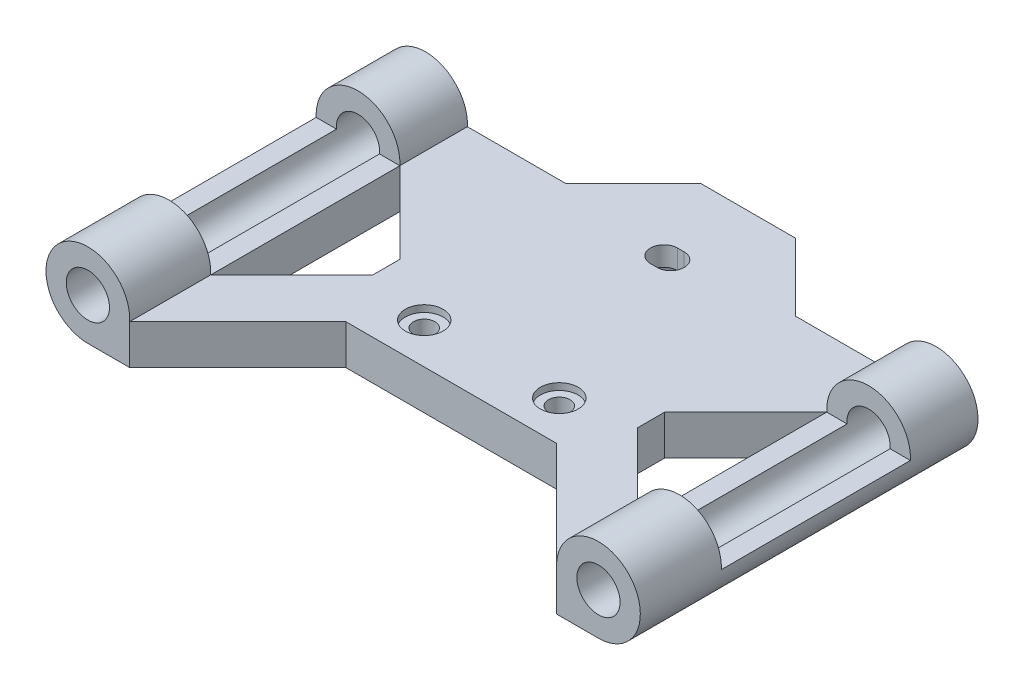
SolidWorks part; units mm, degrees
ref_plane "前视基准面" through (0, 0, 0) normal (0, 0, 1) x (1, 0, 0)
ref_plane "上视基准面" through (0, 0, 0) normal (0, 1, 0) x (1, 0, 0)
ref_plane "右视基准面" through (0, 0, 0) normal (1, 0, 0) x (0, 0, -1)
other "Configuration Table"
sketch "草图1" plane through (0, 0, 0) normal (0, 0, 1) x (1, 0, 0)
  line L0 (-46.6478, 2.4292) -> (-8.8478, 2.4292)
  line L1 (-43.5517, 5.3742) -> (-11.9439, 5.3742)
  line L3 (-37.4778, 5.3742) -> (-18.0178, 5.3742) construction
  circle A0 centre (-46.6478, 5.5292) radius 1.6
  circle A1 centre (-8.8478, 5.5292) radius 1.6
  circle A2 centre (-46.6478, 5.5292) radius 3.1
  circle A3 centre (-8.8478, 5.5292) radius 3.1
  circle A4 centre (-46.6478, 5.5292) radius 1.55 construction
  circle A5 centre (-8.8478, 5.5292) radius 1.525 construction
  dimension "D1" = 3.2
  dimension "D2" = 1.5
extrude "凸台-拉伸1" add sketch "草图1" along normal blind 25 contours A2 A0 | A3 L1 A2 L0 | A3 A1
sketch "草图2" plane through (0, 5.3742, 0) normal (0, 1, 0) x (1, 0, 0)
  line L0 (-19.2478, 0) -> (-24.2478, 5)
  line L1 (-43.5517, 0) -> (-11.9439, 0) construction
  line L2 (-24.2478, 5) -> (-31.2478, 5)
  line L4 (-31.2478, 5) -> (-36.2478, 0)
  line L6 (-27.7478, 17.7449) -> (-27.7478, -46.0927) construction
  line L9 (-43.5478, -25) -> (-43.5478, 0) construction
  line L10 (-11.9478, 0) -> (-11.9478, -25) construction
  line L11 (-36.2478, 0) -> (-19.2478, 0)
  dimension "D1" = 5
  dimension "D2" = 7
  dimension "D3" = 45
extrude "凸台-拉伸2" add sketch "草图2" against normal up to surface (2.945 mm away)
sketch "草图3" plane through (0, 5.3742, 0) normal (0, 1, 0) x (1, 0, 0)
  line L0 (-27.9978, -1) -> (-27.4978, -1) construction
  line L1 (-27.9978, 0) -> (-27.4978, 0)
  line L2 (-27.9978, -2) -> (-27.4978, -2)
  line L3 (-24.2478, 5) -> (-31.2478, 5) construction
  arc A0 (-27.9978, 0) -> (-27.9978, -2) centre (-27.9978, -1) ccw
  arc A1 (-27.4978, -2) -> (-27.4978, 0) centre (-27.4978, -1) ccw
  point P2 (-27.7478, -1)
  point P10 (-27.7478, 5)
  dimension "D1" = 1
  dimension "D2" = 0.5
  dimension "15" = 6
extrude "切除-拉伸1" cut sketch "草图3" against normal through all
sketch "草图5" plane through (0, 2.4292, 0) normal (0, -1, 0) x (-1, 0, 0)
  line L17 (29.8649, -1) -> (28.6813, 1.05)
  line L18 (28.6813, 1.05) -> (26.3142, 1.05)
  line L19 (26.3142, 1.05) -> (25.1306, -1)
  line L20 (25.1306, -1) -> (26.3142, -3.05)
  line L21 (26.3142, -3.05) -> (28.6813, -3.05)
  line L22 (28.6813, -3.05) -> (29.8649, -1)
  line L23 (30.3649, -1) -> (29.1813, 1.05)
  line L24 (29.1813, 1.05) -> (26.8142, 1.05)
  line L25 (26.8142, 1.05) -> (25.6306, -1)
  line L26 (25.6306, -1) -> (26.8142, -3.05)
  line L27 (26.8142, -3.05) -> (29.1813, -3.05)
  line L28 (29.1813, -3.05) -> (30.3649, -1)
  circle A4 centre (27.4978, -1) radius 2.05 construction
  arc A5 (27.4978, 0) -> (27.4978, -2) centre (27.4978, -1) ccw construction
  circle A6 centre (27.9978, -1) radius 2.05 construction
  arc A7 (27.9978, -2) -> (27.9978, 0) centre (27.9978, -1) ccw construction
  line M17 (27.4978, 0) -> (27.9978, 0)
  arc M18 (27.9978, 0) -> (27.9978, -2) centre (27.9978, -1) cw
  line M19 (27.9978, -2) -> (27.4978, -2)
  arc M20 (27.4978, -2) -> (27.4978, 0) centre (27.4978, -1) cw
  dimension "D1" = 4.1
extrude "切除-拉伸4" cut sketch "草图5" against normal blind 1.5 contours L26 L25 L18 L19 L20 L21 | L25 L26 L21 L22 L17 L18 M20 M17 M18 M19 | L27 L28 L23 L24 L17 L22
sketch "草图6" plane through (0, 5.3742, 0) normal (0, 1, 0) x (1, 0, 0)
  line L1 (-27.7478, -17.7348) -> (-27.7478, -33.5164) construction
  line L2 (-43.5517, -25) -> (-11.9439, -25) construction
  circle A0 centre (-32.7478, -14) radius 0.8
  circle A1 centre (-22.7478, -14) radius 0.8
  arc A3 (-27.4978, -2) -> (-27.4978, 0) centre (-27.4978, -1) ccw construction
  point P6 (-27.7478, -25)
  dimension "D2" = 1.6
  dimension "D3" = 13
  dimension "D1" = 10
extrude "切除-拉伸5" cut sketch "草图6" against normal through all
sketch "草图7" plane through (0, 5.3742, 0) normal (0, 1, 0) x (1, 0, 0)
  line L0 (-35.5478, -17) -> (-19.9439, -17)
  line L1 (-19.9439, -17) -> (-11.9439, -25)
  line L2 (-43.5478, -25) -> (-35.5478, -17)
  line L3 (-43.5517, -25) -> (-11.9439, -25) construction
  line L4 (-43.5478, -5) -> (-35.5478, -13)
  line L5 (-43.5478, -25) -> (-43.5478, 0) construction
  line L6 (-35.5478, -13) -> (-35.5478, -17)
  line L7 (-11.9478, -5) -> (-19.9439, -12.9961)
  line L8 (-11.9478, 0) -> (-11.9478, -25) construction
  line L9 (-19.9439, -12.9961) -> (-19.9439, -17)
  line L10 (-43.5478, -19) -> (-35.5478, -11)
  line L11 (-19.9439, -11.0039) -> (-11.9478, -19)
  line L12 (-27.7478, 9.0219) -> (-27.7478, -36.5602) construction
  line L13 (-24.2478, 5) -> (-31.2478, 5) construction
  line L14 (-43.5517, 0) -> (-36.2478, 0) construction
  line L15 (-43.5478, -5) -> (-43.5478, -19)
  line L16 (-11.9478, -5) -> (-11.9478, -19)
  line L17 (-37.5478, -11) -> (-37.5478, -13)
  line L18 (-17.9478, -11) -> (-17.9478, -13)
  circle A0 centre (-32.7478, -14) radius 0.8 construction
  point P26 (-27.7478, 5)
  dimension "D1" = 45
  dimension "D2" = 6
  dimension "D3" = 3
  dimension "D4" = 45
  dimension "D5" = 45
  dimension "D6" = 5
  dimension "D7" = 6
extrude "切除-拉伸6" cut sketch "草图7" against normal through all
sketch "草图9" plane through (-11.9478, 0, 0) normal (-1, 0, 0) x (0, 0, 1)
  line L0 (25, 3.9292) -> (25, 7.1292) construction
  line L1 (25, 3.9292) -> (25, 7.1292)
  line L2 (0, 8.6292) -> (0, 2.4292) construction
  line L3 (25, 3.9292) -> (0, 3.9292)
  line L4 (25, 3.9292) -> (25, 8.6292)
  line L5 (25, 8.6292) -> (0, 8.6292)
  line L6 (0, 3.9292) -> (0, 8.6292)
  line L7 (25, 8.6292) -> (0, 8.6292) construction
  line L8 (5, 5.3742) -> (19, 5.3742) construction
  line L9 (5, 5.3742) -> (19, 5.3742)
  line L12 (19, 5.3742) -> (5, 5.3742)
  line L13 (5, 5.3742) -> (5, 2.4292)
  line L14 (5, 2.4292) -> (19, 2.4292)
  line L15 (19, 2.4292) -> (19, 5.3742)
  line L17 (5, 8.6292) -> (5, 2.4292)
  line L18 (5, 2.4292) -> (19, 2.4292)
  line L19 (19, 2.4292) -> (19, 8.6292)
  line M5 (19, 5.3742) -> (5, 5.3742)
  dimension "D1" = 0
extrude "切除-拉伸9" cut sketch "草图9" against normal through all contours L19 L5 L17 M5
ref_plane "基准面1" through (-27.7478, 0, 0) normal (1, 0, 0) x (0, 0, -1)
mirror "镜向1" about plane through (-27.7478, 0, 0) normal (1, 0, 0) of "切除-拉伸9"
sketch "草图10" plane through (0, 5.3742, 0) normal (0, 1, 0) x (1, 0, 0)
  circle A0 centre (-22.7478, -14) radius 1.4
  circle A1 centre (-32.7478, -14) radius 1.4
  circle A2 centre (-22.7478, -14) radius 0.8 construction
  circle A3 centre (-32.7478, -14) radius 0.8 construction
  dimension "D1" = 2.8
extrude "切除-拉伸11" cut sketch "草图10" against normal blind 0.5
